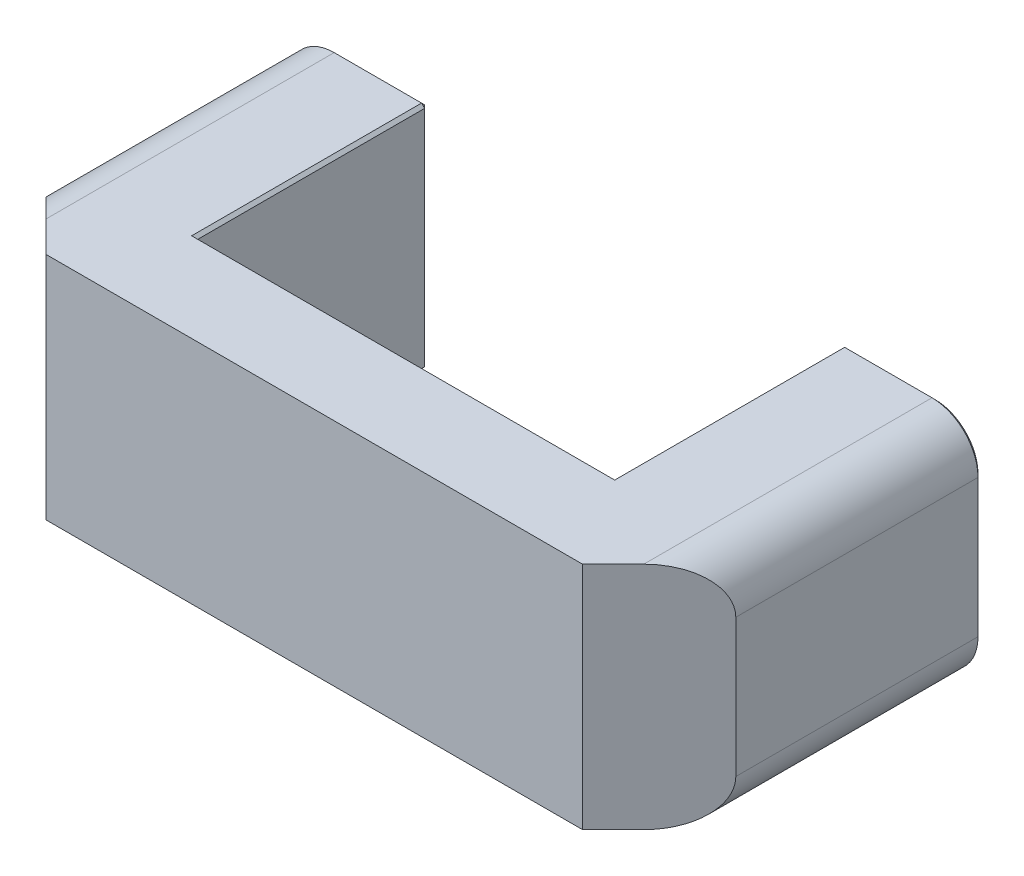
SolidWorks part; units mm, degrees
ref_plane "Front Plane" through (0, 0, 0) normal (0, 0, 1) x (1, 0, 0)
ref_plane "Top Plane" through (0, 0, 0) normal (0, 1, 0) x (1, 0, 0)
ref_plane "Right Plane" through (0, 0, 0) normal (1, 0, 0) x (0, 0, -1)
sketch "Sketch1" plane through (0, 0, 0) normal (0, 1, 0) x (1, 0, 0)
  line L0 (-45, 30) -> (-45, -12)
  line L1 (-45, -12) -> (45, -12)
  line L2 (45, -12) -> (45, 30)
  line L3 (45, 30) -> (27.2, 30)
  line L4 (27.2, 30) -> (27.2, 0)
  line L5 (27.2, 0) -> (-27.2, 0)
  line L6 (-27.2, 0) -> (-27.2, 30)
  line L7 (-27.2, 30) -> (-45, 30)
  line L8 (0, -12) -> (0, 0) construction
  dimension "D1" = 54.4
  dimension "D2" = 90
  dimension "D3" = 12
  dimension "D4" = 30
extrude "Boss-Extrude1" add sketch "Sketch1" along normal blind 30
chamfer "Chamfer1" distance 10 angle 45 2 edges at (-45, 15, 12) (45, 15, 12)
fillet "Fillet1" radius 6 4 edges at (-45, 30, -14) (-45, 0, -14) (45, 30, -14) (45, 0, -14)
hole_wizard "Ø5.0mm Dowel Hole1" positions "Sketch4" profile "Sketch6" hole size "Ø5.0" standard "ISO"
sketch "Sketch4" plane through (0, 0, -30) normal (0, 0, -1) x (-1, 0, 0)
  line L0 (-45, 15) -> (-27.2, 15) construction
  line L1 (-45, 24) -> (-45, 6) construction
  line L2 (-27.2, 30) -> (-27.2, 0) construction
  line L4 (27.2, 15) -> (45, 15) construction
  line L5 (27.2, 30) -> (27.2, 0) construction
  line L6 (45, 24) -> (45, 6) construction
  line L7 (0, 30) -> (0, 0) construction
  line L8 (-27.2, 30) -> (27.2, 30) construction
  line L9 (-27.2, 0) -> (27.2, 0) construction
  line L11 (36.1, 15) -> (36.1, 30) construction
  line L12 (27.2, 30) -> (39, 30) construction
  point P34 (36.1, 22.5)
  point P37 (0, 0)
  point P38 (0, 0)
  point P39 (36.1, 7.5)
  point P40 (0, 0)
  point P41 (-36.1, 22.5)
  point P42 (-36.1, 7.5)
sketch "Sketch6" plane through (36.1, 7.5, -30) normal (1, 0, 0) x (0, 1, 0)
  line L0 (0, 0) -> (0, 13.5022)
  line L1 (0, 13.5022) -> (2.5, 12)
  line L2 (2.5, 12) -> (2.5, 0)
  line L5 (2.5, 0) -> (0, 0)
  line L10 (0, 13.5022) -> (-2.5, 12) construction
  line L11 (0, -6.35) -> (0, 107.95) construction
  dimension "Hole Dia." = 5
  dimension "Hole Depth" = 12
  dimension "Drill Angle" = 118
chamfer "Chamfer2" distance 0.4 angle 45 22 edges at (33.1, 0, -30) (-33.1, 30, -30) (43.2426, 1.7574, -30) (-43.2426, 28.2426, -30) (45, 15, -30) (-45, 15, -30) (43.2426, 28.2426, -30) (-43.2426, 1.7574, -30) (33.1, 30, -30) (-27.2, 30, -15) (-33.1, 0, -30) (-27.2, 15, -30) (-27.2, 0, -15) (0, 0, 0) (0, 30, 0) (27.2, 30, -15) (27.2, 15, -30) (27.2, 0, -15) (-38.6, 7.5, -30) (-38.6, 22.5, -30) (33.6, 7.5, -30) (33.6, 22.5, -30)
